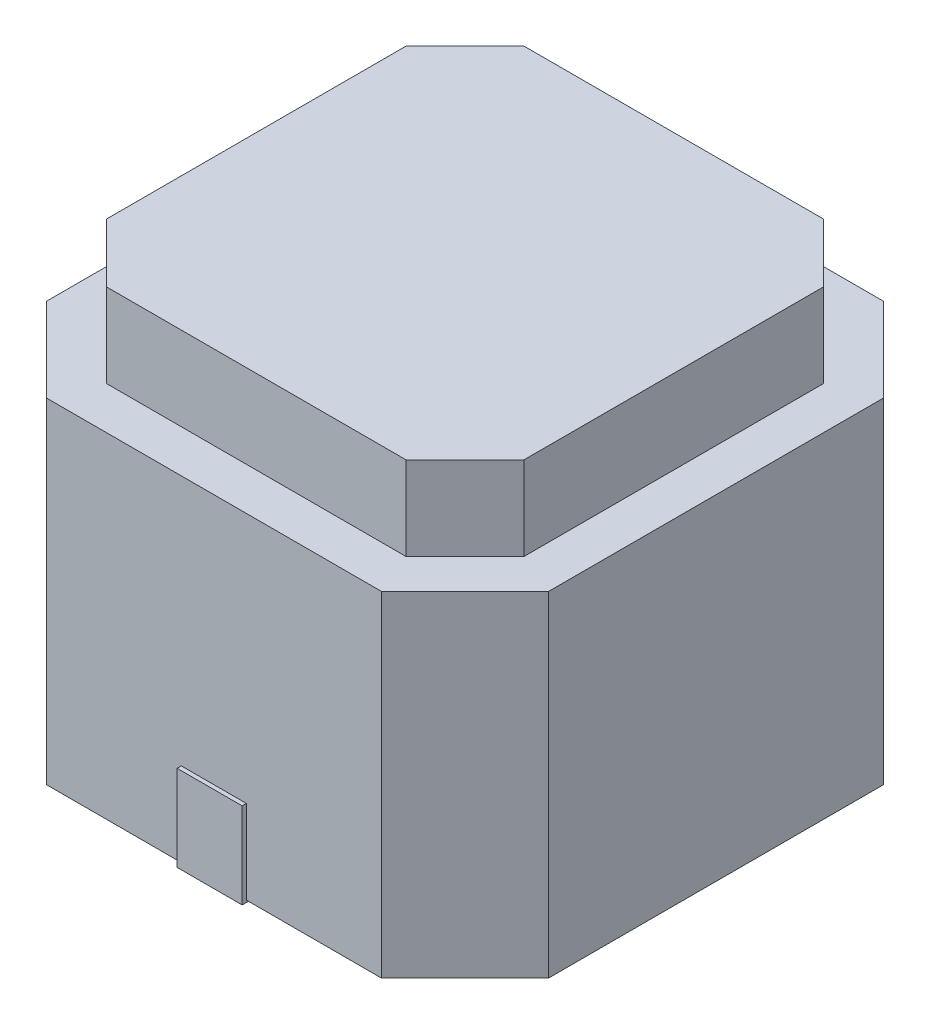
SolidWorks part; units mm, degrees
ref_plane "Front Plane" through (0, 0, 0) normal (0, 0, 1) x (1, 0, 0)
ref_plane "Top Plane" through (0, 0, 0) normal (0, 1, 0) x (1, 0, 0)
ref_plane "Right Plane" through (0, 0, 0) normal (1, 0, 0) x (0, 0, -1)
sketch "Sketch1" plane through (0, 0, 0) normal (0, 1, 0) x (1, 0, 0)
  line L0 (-3, 2) -> (-2, 3)
  line L1 (-2, 3) -> (2, 3)
  line L2 (-3, 2) -> (-3, -2)
  line L3 (-2, -3) -> (2, -3)
  line L4 (3, 2) -> (3, -2)
  line L5 (2, 3) -> (3, 2)
  line L6 (2, -3) -> (3, -2)
  line L7 (-3, -2) -> (-2, -3)
  point P0 (-3, 3)
  point P1 (3, -3)
  point P2 (-3, -3)
  point P3 (3, 3)
  dimension "D1" = 6
extrude "Boss-Extrude1" add sketch "Sketch1" along normal blind 5
sketch "Sketch2" plane through (0, 5, 0) normal (0, 1, 0) x (1, 0, 0)
  line L16 (2.492, 1.7896) -> (1.7896, 2.492)
  line L17 (1.7896, 2.492) -> (-1.7896, 2.492)
  line L18 (-1.7896, 2.492) -> (-2.492, 1.7896)
  line L19 (-2.492, 1.7896) -> (-2.492, -1.7896)
  line L20 (-2.492, -1.7896) -> (-1.7896, -2.492)
  line L21 (-1.7896, -2.492) -> (1.7896, -2.492)
  line L22 (1.7896, -2.492) -> (2.492, -1.7896)
  line L23 (2.492, -1.7896) -> (2.492, 1.7896)
  line L24 (2.492, 1.7896) -> (1.7896, 2.492)
  line L25 (1.7896, 2.492) -> (-1.7896, 2.492)
  line L26 (-1.7896, 2.492) -> (-2.492, 1.7896)
  line L27 (-2.492, 1.7896) -> (-2.492, -1.7896)
  line L28 (-2.492, -1.7896) -> (-1.7896, -2.492)
  line L29 (-1.7896, -2.492) -> (1.7896, -2.492)
  line L30 (1.7896, -2.492) -> (2.492, -1.7896)
  line L31 (2.492, -1.7896) -> (2.492, 1.7896)
  line M9 (3, 2) -> (2, 3)
  line M10 (2, 3) -> (-2, 3)
  line M11 (-2, 3) -> (-3, 2)
  line M12 (-3, 2) -> (-3, -2)
  line M13 (-3, -2) -> (-2, -3)
  line M14 (-2, -3) -> (2, -3)
  line M15 (2, -3) -> (3, -2)
  line M16 (3, -2) -> (3, 2)
  dimension "D1" = 0.508
extrude "Cut-Extrude1" cut sketch "Sketch2" against normal blind 1 contours L31 L30 L29 L28 L27 L26 L25 L24 M16 M9 M10 M11 M12 M13 M14 M15
sketch "Sketch3" plane through (0, 0, 0) normal (0, -1, 0) x (1, 0, 0)
  line L0 (0, 1.3708) -> (0, -1.3708) construction
  line L1 (0.3886, 1.3708) -> (-0.3886, 1.3708)
  line L2 (0.3886, 1.3708) -> (0.3886, 3.05)
  line L3 (0.3886, 3.05) -> (-0.3886, 3.05)
  line L4 (-0.3886, 1.3708) -> (-0.3886, 3.05)
  line L5 (-0.3886, -1.3708) -> (0.3886, -1.3708)
  line L6 (-0.3886, -1.3708) -> (-0.3886, -3.05)
  line L7 (-0.3886, -3.05) -> (0.3886, -3.05)
  line L8 (2, -3) -> (3, -2)
  line L9 (3, -2) -> (3, 2)
  line L10 (3, 2) -> (2, 3)
  line L11 (2, 3) -> (-2, 3)
  line L12 (-2, 3) -> (-3, 2)
  line L13 (-3, 2) -> (-3, -2)
  line L14 (-3, -2) -> (-2, -3)
  line L15 (-2, -3) -> (2, -3)
  line L16 (2, -3) -> (3, -2)
  line L17 (3, -2) -> (3, 2)
  line L18 (3, 2) -> (2, 3)
  line L19 (2, 3) -> (-2, 3)
  line L20 (-2, 3) -> (-3, 2)
  line L21 (-3, 2) -> (-3, -2)
  line L22 (-3, -2) -> (-2, -3)
  line L23 (-2, -3) -> (2, -3)
  line L24 (0.3886, -1.3708) -> (0.3886, -3.05)
  point P16 (0, -1.3708)
  point P18 (0, 1.3708)
  line M21 (2, 3) -> (-2, 3)
  line M25 (-2, -3) -> (2, -3)
  dimension "D2" = 6.1
  dimension "D1" = 0
extrude "Boss-Extrude2" add sketch "Sketch3" against normal blind 1 and the other way blind 0.0254 contours L24 L5 L6 M25 | L4 L1 L2 M21
